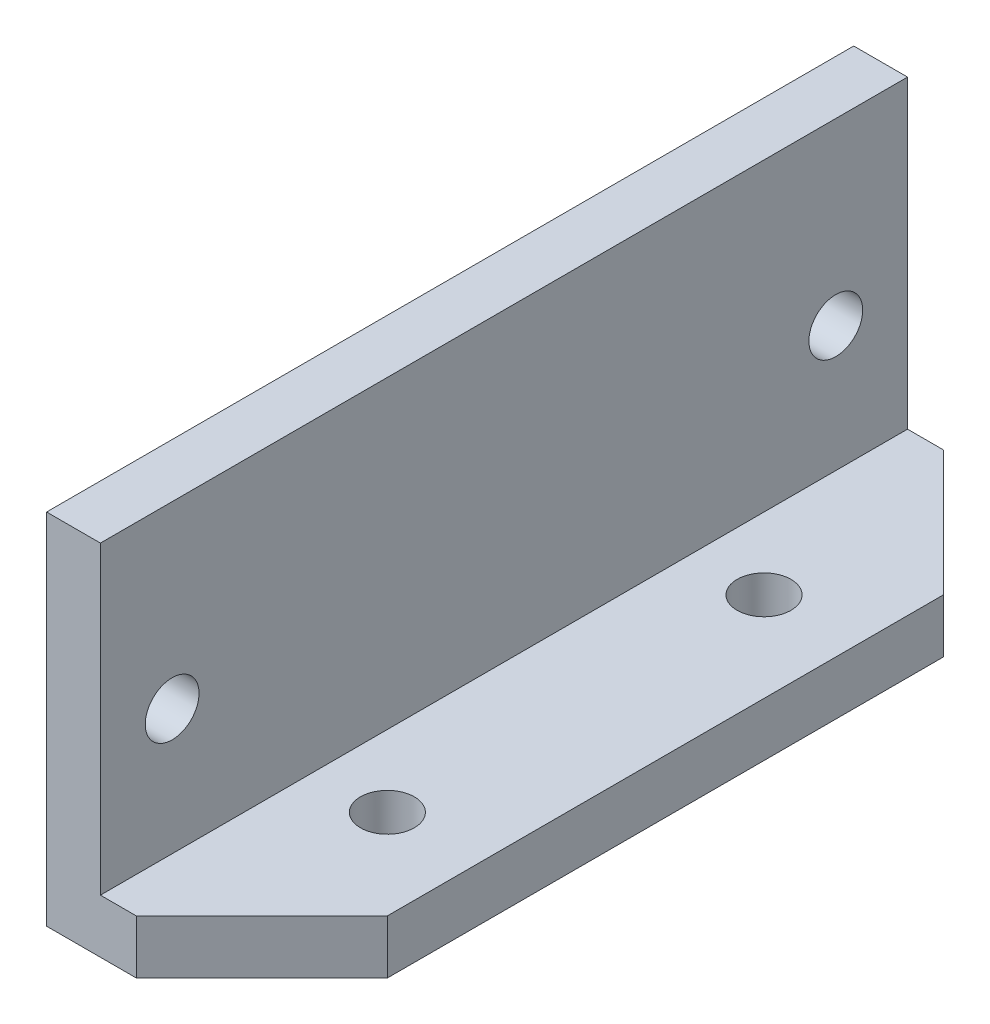
SolidWorks part; units mm, degrees
ref_plane "前视基准面" through (0, 0, 0) normal (0, 0, 1) x (1, 0, 0)
ref_plane "上视基准面" through (0, 0, 0) normal (0, 1, 0) x (1, 0, 0)
ref_plane "右视基准面" through (0, 0, 0) normal (1, 0, 0) x (0, 0, -1)
sketch "草图1" plane through (0, 0, 0) normal (0, 0, 1) x (1, 0, 0)
  line L0 (-2.0091, 20) -> (-2.0091, 3)
  line L1 (-2.0091, 3) -> (6.9909, 3)
  line L2 (6.9909, 3) -> (6.9909, 0)
  line L3 (6.9909, 0) -> (-5.0091, 0)
  line L4 (-5.0091, 0) -> (-5.0091, 20)
  line L5 (-5.0091, 20) -> (-2.0091, 20)
  dimension "D1" = 3
  dimension "D2" = 3
  dimension "D3" = 20
  dimension "D4" = 12
extrude "凸台-拉伸1" add sketch "草图1" along normal blind 45
sketch "草图2" plane through (-5.0091, 0, 0) normal (-1, 0, 0) x (0, 0, 1)
  line L0 (22.5, 20) -> (22.5, 0) construction
  line L1 (45, 20) -> (0, 20) construction
  line L2 (45, 0) -> (0, 0) construction
  circle A0 centre (4, 10) radius 1.5
  circle A1 centre (41, 10) radius 1.5
  dimension "D1" = 37
  dimension "D2" = 3
  dimension "D3" = 10
sketch "草图3" plane through (0, 0, 0) normal (0, -1, 0) x (1, 0, 0)
  line L0 (-5.0091, 22.5) -> (6.9909, 22.5) construction
  line L1 (-5.0091, 45) -> (-5.0091, 0) construction
  line L2 (6.9909, 45) -> (6.9909, 0) construction
  circle A0 centre (1.9909, 33) radius 1.5
  circle A1 centre (1.9909, 12) radius 1.5
  dimension "D1" = 3
  dimension "D2" = 21
  dimension "D3" = 7
extrude "切除-拉伸1" cut sketch "草图3" against normal through all
extrude "切除-拉伸2" cut sketch "草图2" against normal through all
sketch "草图4" plane through (0, 0, 0) normal (0, -1, 0) x (1, 0, 0)
  line L0 (-5.0091, 22.5) -> (6.9909, 22.5) construction
  line L1 (-5.0091, 45) -> (-5.0091, 0) construction
  line L2 (6.9909, 45) -> (6.9909, 0) construction
  line L3 (-0.0091, 45) -> (6.9909, 38)
  line L4 (-5.0091, 45) -> (6.9909, 45) construction
  line L5 (6.9909, 38) -> (6.9909, 45)
  line L6 (6.9909, 45) -> (-0.0091, 45)
  line L7 (6.9909, 7) -> (6.9909, 0)
  line L8 (-0.0091, 0) -> (6.9909, 7)
  line L9 (6.9909, 0) -> (-0.0091, 0)
  dimension "D1" = 7
  dimension "D2" = 7
extrude "切除-拉伸3" cut sketch "草图4" against normal through all
